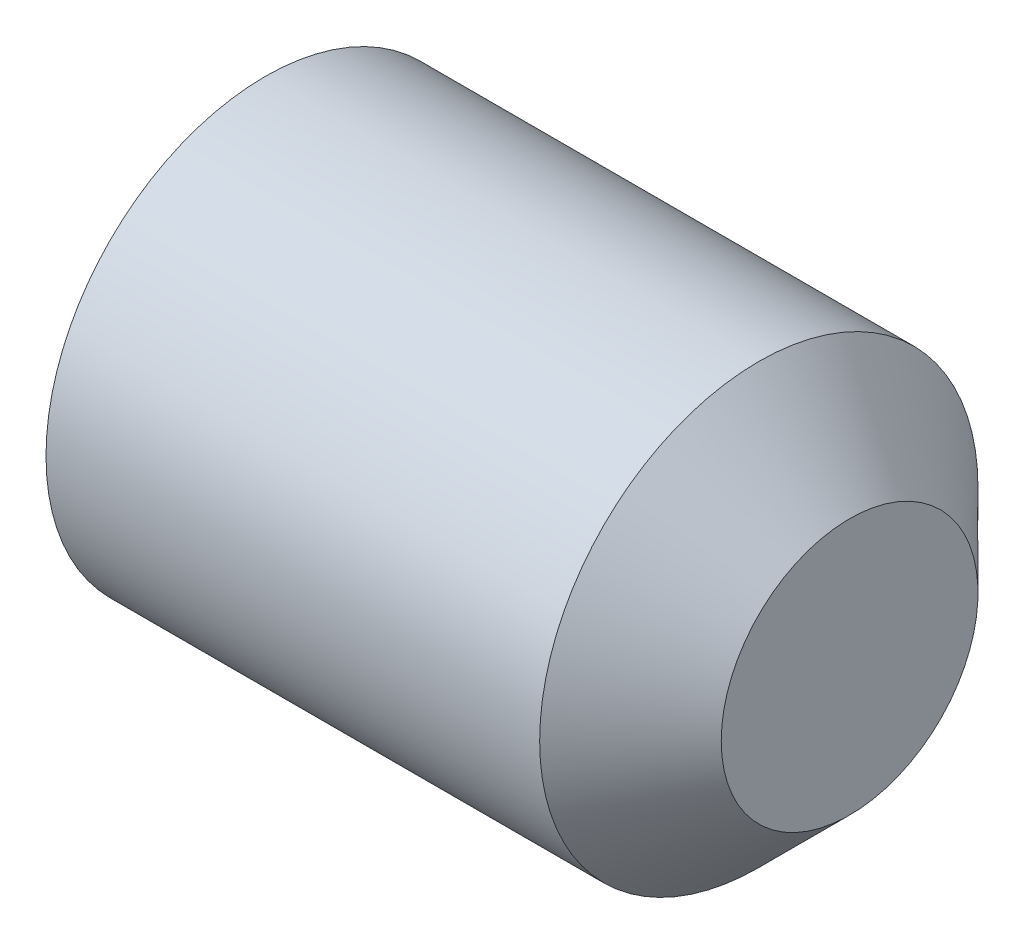
SolidWorks part; units mm, degrees
material "AISI 304"
ref_plane "Front Plane" through (0, 0, 0) normal (0, 0, 1) x (1, 0, 0)
ref_plane "Top Plane" through (0, 0, 0) normal (0, 1, 0) x (1, 0, 0)
ref_plane "Right Plane" through (0, 0, 0) normal (1, 0, 0) x (0, 0, -1)
sketch "Sketch1" plane through (0, 0, 0) normal (0, 0, 1) x (1, 0, 0)
  line L0 (0, 0) -> (105.4919, 0) construction
  line L1 (4, 0.8787) -> (4, 0)
  line L2 (4, 0.8787) -> (3.3787, 1.5)
  line L3 (3.3787, 1.5) -> (0, 1.5)
  line L4 (0, 1.5) -> (0, 0)
  line L5 (0, 0) -> (4, 0)
  dimension "D1" = 3
  dimension "D2" = 4
  dimension "D3" = 45
  dimension "D4" = 90
revolve "Revolve1" add sketch "Sketch1" angle 360 about L0
sketch "Sketch2" plane through (0, 0, 0) normal (-1, 0, 0) x (0, 0, 1)
  line L1 (-0.433, 0.75) -> (-0.866, 0)
  line L2 (-0.866, 0) -> (-0.433, -0.75)
  line L3 (-0.433, -0.75) -> (0.433, -0.75)
  line L4 (0.433, -0.75) -> (0.866, 0)
  line L5 (0.866, 0) -> (0.433, 0.75)
  line L6 (0.433, 0.75) -> (-0.433, 0.75)
  circle A0 centre (0, 0) radius 0.75 construction
  dimension "D1" = 1.5
extrude "Cut-Extrude1" cut sketch "Sketch2" against normal blind 1.5
